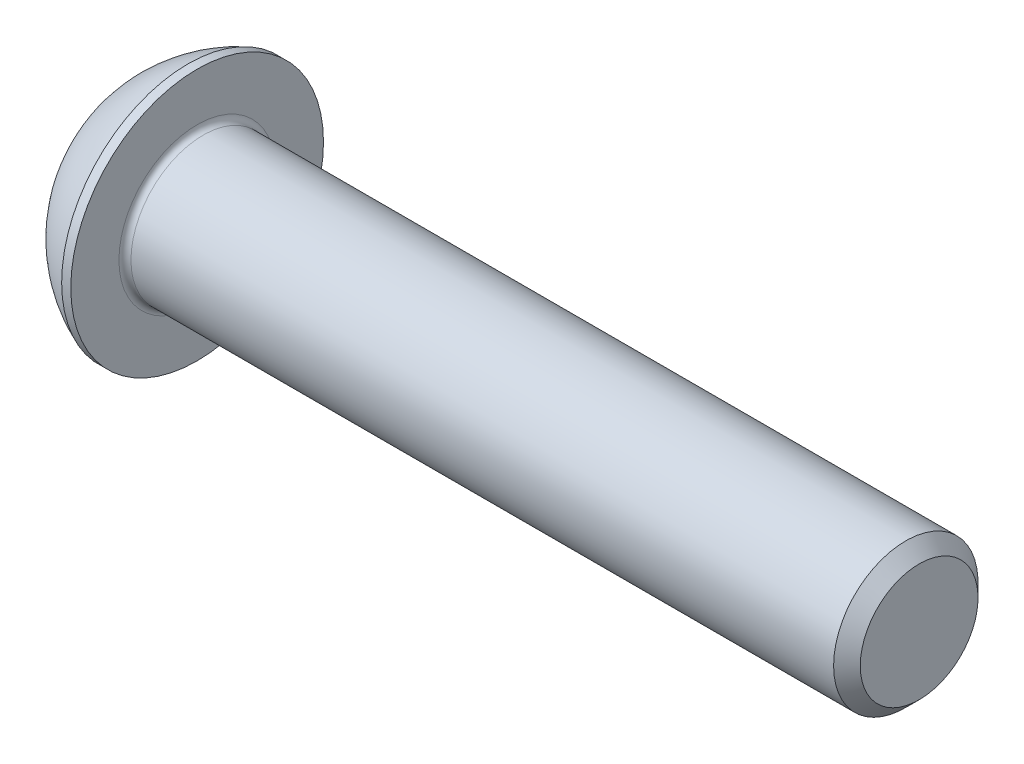
SolidWorks part; units mm, degrees
ref_plane "Plane1" through (0, 0, 0) normal (0, 0, 1) x (1, 0, 0)
ref_plane "Plane2" through (0, 0, 0) normal (0, 1, 0) x (1, 0, 0)
ref_plane "Plane3" through (0, 0, 0) normal (1, 0, 0) x (0, 0, -1)
sketch "BodySke" plane through (0, 0, 0) normal (0, 0, 1) x (1, 0, 0)
  line L0 (33.3, 0) -> (33.3, 2.4455)
  line L1 (32.7455, 3) -> (3.3, 3)
  line L2 (3.3, 3) -> (3.3, 5.25)
  line L3 (3.3, 5.25) -> (2.92, 5.25)
  line L4 (0, 0) -> (101.6, 0) construction
  line L5 (3.3, -5.25) -> (2.92, -5.25) construction
  line L6 (55.6768, -3) -> (3.3, -3) construction
  line L7 (33.3, 0) -> (0, 0)
  line L8 (0, 2.625) -> (0, -2.625) construction
  line L9 (0, 0) -> (0, 2.625)
  line L10 (33.3, 2.4455) -> (32.7455, 3)
  line L11 (33.3, -2.4455) -> (32.7455, -3) construction
  line L12 (4.3, 9.525) -> (4.3, -3) construction
  line L13 (23.3, 9.525) -> (23.3, -3) construction
  arc A1 (0, 2.625) -> (2.92, 5.25) centre (4.9997, 0) cw
  dimension "Diameter" = 6
  dimension "Length" = 30
  dimension "Head_dia" = 10.5
  dimension "D1" = 5.25
  dimension "Head_ht" = 3.3
  dimension "Head_side_ht" = 0.38
  dimension "Minor_dia" = 4.891
  dimension "Body_ch_ang" = 45
  dimension "Advance" = 1
  dimension "Thread_nom" = 10
revolve "BaseBody" add sketch "BodySke" angle 360 about L4
cosmetic thread "ThreadCosmetic" [suppressed] parameters "Thread_length"=10, "Thread_minor"=4.891
fillet "Fillet1" radius 0.25 1 edges at (3.3, 0, 3)
sketch "Sketch2" plane through (0, 0, 0) normal (0, 0, 1) x (1, 0, 0)
  line L0 (0, 2) -> (2.08, 2)
  line L1 (2.08, 2) -> (3.2347, 0)
  line L3 (3.2347, 0) -> (0, 0)
  line L4 (0, 0) -> (0, 2)
  line L5 (0, -2) -> (2.08, -2) construction
  line L6 (0, 0) -> (47.625, 0) construction
  dimension "D2" = 60
  dimension "PreBroach_depth" = 2.08
  dimension "PreBroach_dia" = 4
revolve "PreBroach" cut sketch "Sketch2" angle 360 about L6
sketch "Sketch3" plane through (0, 0, 0) normal (1, 0, 0) x (0, 0, -1)
  line L0 (-2, -1.1547) -> (-2, 1.1547)
  line L1 (-2, 1.1547) -> (0, 2.3094)
  line L2 (0, 2.3094) -> (2, 1.1547)
  line L3 (2, 1.1547) -> (2, -1.1547)
  line L4 (2, -1.1547) -> (0, -2.3094)
  line L5 (0, -2.3094) -> (-2, -1.1547)
  dimension "Hex_size" = 4
  dimension "D3" = 4
  dimension "D1" = 2
  dimension "D2" = 2
extrude "Hex" cut sketch "Sketch3" along normal blind 2.08
sketch "ThdSchSke" plane through (0, 0, 0) normal (0, 0, 1) x (1, 0, 0)
  line L0 (23.3, -2.4455) -> (22.9117, -3)
  line L1 (23.3, -2.4455) -> (23.6883, -3)
  line L2 (23.6883, -3) -> (23.6883, -3.75)
  line L3 (-3.175, 0) -> (5.1513, 0) construction
  line L5 (23.6883, -3.75) -> (22.9117, -3.75)
  line L6 (22.9117, -3.75) -> (22.9117, -3)
  dimension "Diameter" = 6
  dimension "Thread_minor" = 4.891
  dimension "SideAngle" = 55
  dimension "VeeAngle" = 70
  dimension "Overcut" = 7.5
  dimension "Start" = 23.3
revolve "ThreadSchematic" [suppressed] cut sketch "ThdSchSke" angle 360 about L3
pattern_linear "ThdSchPat" [suppressed]
equation "\"D1@BodySke\" = \"Head_dia@BodySke\" * .5"
equation "\"Thread_minor@ThreadCosmetic\" = \"Minor_dia@BodySke\""
equation "\"D1@Sketch3\" = \"Hex_size@Sketch3\" / 2"
equation "\"D2@Sketch3\" = \"D1@Sketch3\""
equation "\"D3@Sketch3\" = \"Hex_size@Sketch3\""
equation "\"Thread_length@ThreadCosmetic\" = ((sgn( (\"Length@BodySke\" - \"Advance@BodySke\" * 2.0) - \"Thread_nom@BodySke\" )-1)*( (\"Length@BodySke\" - \"Advance@BodySke\" * 2.0) - \"Thread_nom@BodySke\" ))/-2+ \"Thread_nom@BodySke\""
equation "\"Thread_minor@ThdSchSke\" = \"Minor_dia@BodySke\""
equation "\"Diameter@ThdSchSke\" = \"Diameter@BodySke\""
equation "\"Overcut@ThdSchSke\" = \"Diameter@BodySke\" * 1.25"
equation "\"Start@ThdSchSke\" = \"Head_ht@BodySke\" + \"Length@BodySke\" - \"Thread_length@ThreadCosmetic\"  '---Non-countersunk---"
equation "\"Num_threads@ThdSchPat\" = int( \"Thread_length@ThreadCosmetic\" / \"Advance@BodySke\" + 0.999 )  + 1"
equation "\"Advance@ThdSchPat\" = \"Thread_length@ThreadCosmetic\" /  (\"Num_threads@ThdSchPat\" - 1) 'relax it"
equation "\"Num_threads@ThdSchPat\" = \"Num_threads@ThdSchPat\" - sgn( \"Num_threads@ThdSchPat\" - 1) '---chamfered tips only---"
